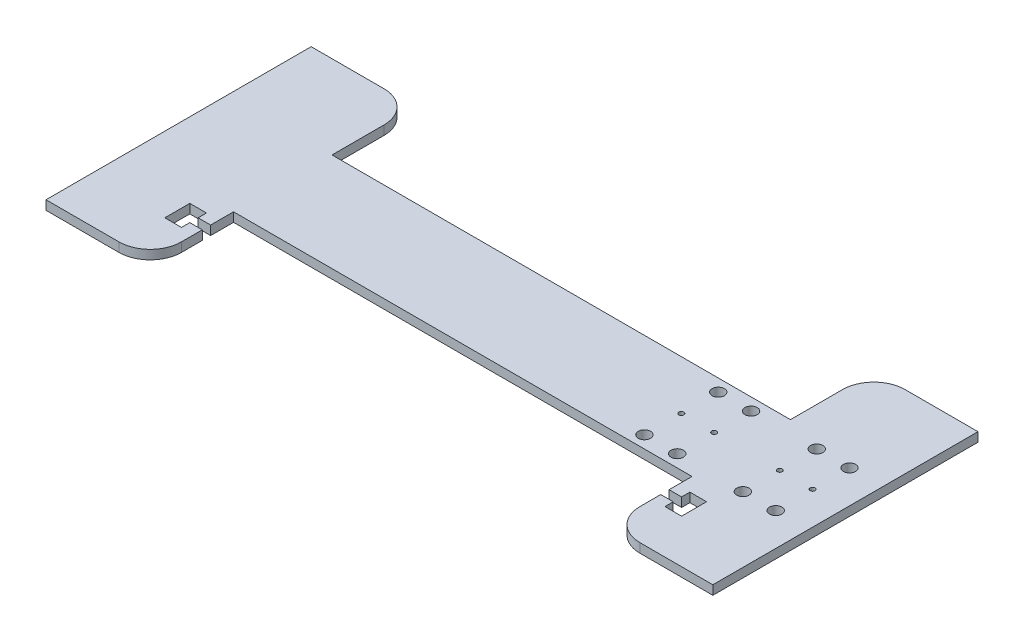
SolidWorks part; units mm, degrees
material "Beech"
ref_plane "Front Plane" through (0, 0, 0) normal (0, 0, 1) x (1, 0, 0)
ref_plane "Top Plane" through (0, 0, 0) normal (0, 1, 0) x (1, 0, 0)
ref_plane "Right Plane" through (0, 0, 0) normal (1, 0, 0) x (0, 0, -1)
sketch "Sketch1" plane through (0, 0, 0) normal (0, 1, 0) x (1, 0, 0)
  line L0 (203.2, 161.6) -> (203.2, 50.8) construction
  line L1 (0, 0) -> (406.4, 0)
  line L2 (0, 0) -> (0, 161.6)
  line L3 (0, 161.6) -> (406.4, 161.6)
  line L4 (406.4, 0) -> (406.4, 161.6)
  line L5 (63.5, 0) -> (342.9, 0)
  line L6 (63.5, 0) -> (63.5, 50.8)
  line L7 (63.5, 50.8) -> (342.9, 50.8)
  line L8 (342.9, 0) -> (342.9, 50.8)
  line L9 (203.2, 50.8) -> (203.2, 0) construction
  line L10 (0, 80.8) -> (406.4, 80.8) construction
  line L11 (342.9, 161.6) -> (342.9, 110.8)
  line L12 (63.5, 110.8) -> (342.9, 110.8)
  line L13 (63.5, 161.6) -> (63.5, 110.8)
  line L14 (350.52, 41.91) -> (360.68, 41.91)
  line L15 (342.9, 31.75) -> (350.52, 31.75)
  line L16 (342.9, 31.75) -> (342.9, 36.83)
  line L17 (342.9, 36.83) -> (350.52, 36.83)
  line L18 (350.52, 31.75) -> (350.52, 36.83) construction
  line L19 (350.52, 34.29) -> (360.68, 34.29) construction
  line L20 (350.52, 41.91) -> (350.52, 26.67)
  line L21 (350.52, 26.67) -> (360.68, 26.67)
  line L22 (360.68, 41.91) -> (360.68, 26.67)
  line L23 (55.88, 26.67) -> (45.72, 26.67)
  line L24 (55.88, 41.91) -> (55.88, 26.67)
  line L25 (63.5, 36.83) -> (55.88, 36.83)
  line L26 (63.5, 31.75) -> (55.88, 31.75)
  line L27 (55.88, 34.29) -> (45.72, 34.29) construction
  line L28 (55.88, 41.91) -> (45.72, 41.91)
  line L29 (45.72, 41.91) -> (45.72, 26.67)
  dimension "D2" = 406.4
  dimension "D3" = 63.5
  dimension "D4" = 63.5
  dimension "D5" = 50.8
  dimension "D6" = 7.62
  dimension "D7" = 5.08
  dimension "D8" = 31.75
  dimension "D9" = 7.62
  dimension "D10" = 10.16
  dimension "D11" = 60
extrude "Boss-Extrude1" add sketch "Sketch1" along normal blind 5.588 contours L13 L3 L2 L1 L6 L7 L8 L4 L11 L12
fillet "Fillet1" radius 19.05 4 edges at (342.9, 2.794, -161.6) (63.5, 2.794, -161.6) (342.9, 2.794, 0) (63.5, 2.794, 0)
sketch "Sketch2" plane through (0, 5.588, 0) normal (0, 1, 0) x (1, 0, 0)
  line L0 (406.4, 80.8) -> (366.4, 80.8) construction
  line L1 (406.4, 0) -> (406.4, 161.6) construction
  line L2 (366.4, 80.8) -> (366.4, 103.3) construction
  line L3 (366.4, 103.3) -> (386.4, 103.3) construction
  line L4 (386.4, 103.3) -> (386.4, 80.8) construction
  line L5 (326.4, 80.8) -> (366.4, 80.8) construction
  circle A0 centre (366.4, 80.8) radius 1.5
  circle A1 centre (386.4, 80.8) radius 1.5
  circle A2 centre (366.4, 103.3) radius 3.75
  circle A3 centre (386.4, 103.3) radius 3.75
  circle A4 centre (386.4, 58.3) radius 3.75
  circle A5 centre (366.4, 58.3) radius 3.75
  circle A6 centre (306.4, 103.3) radius 3.75
  circle A7 centre (326.4, 103.3) radius 3.75
  circle A8 centre (326.4, 80.8) radius 1.5
  circle A9 centre (306.4, 80.8) radius 1.5
  circle A10 centre (306.4, 58.3) radius 3.75
  circle A11 centre (326.4, 58.3) radius 3.75
  dimension "D1" = 7.5
  dimension "D2" = 3
  dimension "D3" = 20
  dimension "D4" = 22.5
  dimension "D5" = 20
  dimension "D7" = 60
  dimension "D6" = 2
extrude "Cut-Extrude1" cut sketch "Sketch2" against normal through all
